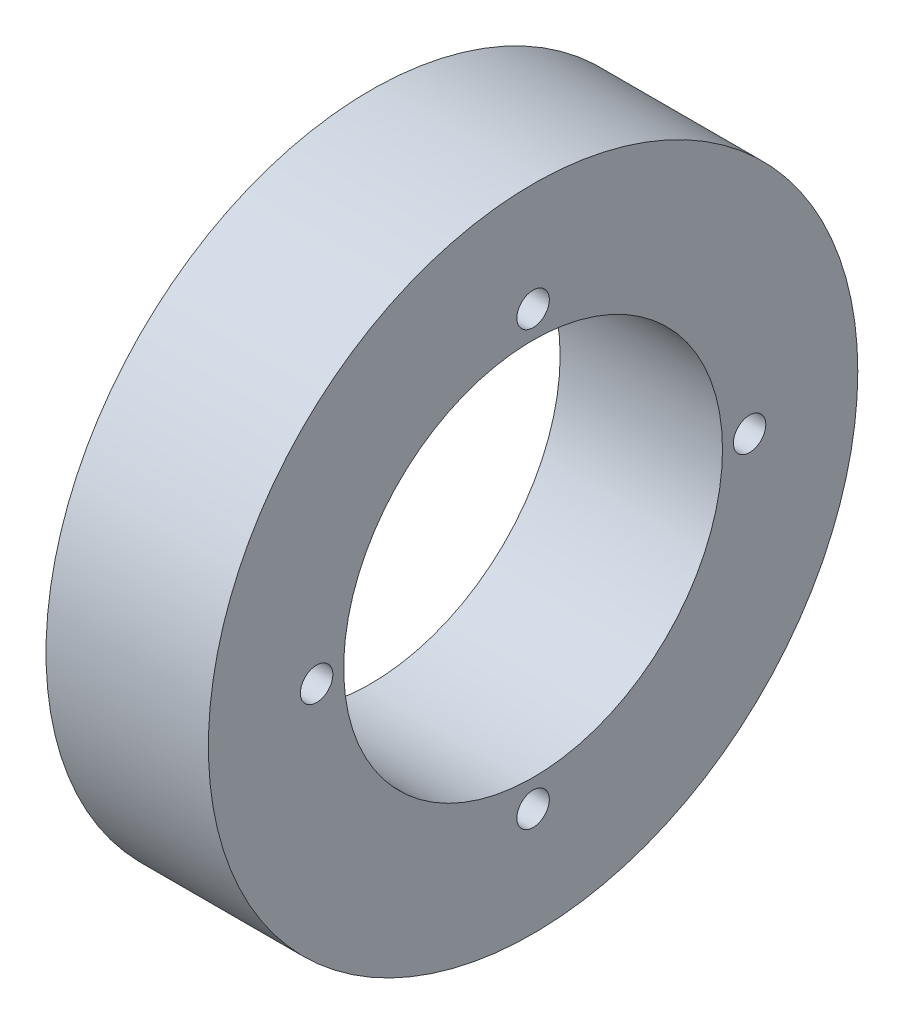
SolidWorks part; units mm, degrees
ref_plane "Front Plane" through (0, 0, 0) normal (0, 0, 1) x (1, 0, 0)
ref_plane "Top Plane" through (0, 0, 0) normal (0, 1, 0) x (1, 0, 0)
ref_plane "Right Plane" through (0, 0, 0) normal (1, 0, 0) x (0, 0, -1)
sketch "Sketch1" plane through (0, 0, 0) normal (1, 0, 0) x (0, 0, -1)
  circle A0 centre (0, 0) radius 30
  circle A1 centre (0, 0) radius 17.5
  dimension "D1" = 60
  dimension "D2" = 35
extrude "Boss-Extrude1" add sketch "Sketch1" along normal mid plane 15
sketch "Sketch2" plane through (7.5, 0, 0) normal (1, 0, 0) x (0, 0, -1)
  circle A2 centre (0, 0) radius 20 construction
  circle A3 centre (0, 20) radius 1.5
  circle A4 centre (20, 0) radius 1.5
  circle A5 centre (0, -20) radius 1.5
  circle A6 centre (-20, 0) radius 1.5
  point P13 (0, 0)
  dimension "D1" = 40
  dimension "D2" = 3
  dimension "D4" = 20
  dimension "D5" = 20
  dimension "D3" = 4
extrude "Cut-Extrude1" cut sketch "Sketch2" against normal through all
equation "\"shaft-diameter\" =20mm"
equation "\"key-length\"=12mm"
equation "\"key-width\"=4mm"
equation "\"flippershaft-wormgear-diameter\" = 35mm"
equation "\"D4@Sketch2\"=\"D1@Sketch2\"/2"
equation "\"D5@Sketch2\"=\"D1@Sketch2\"/2"
